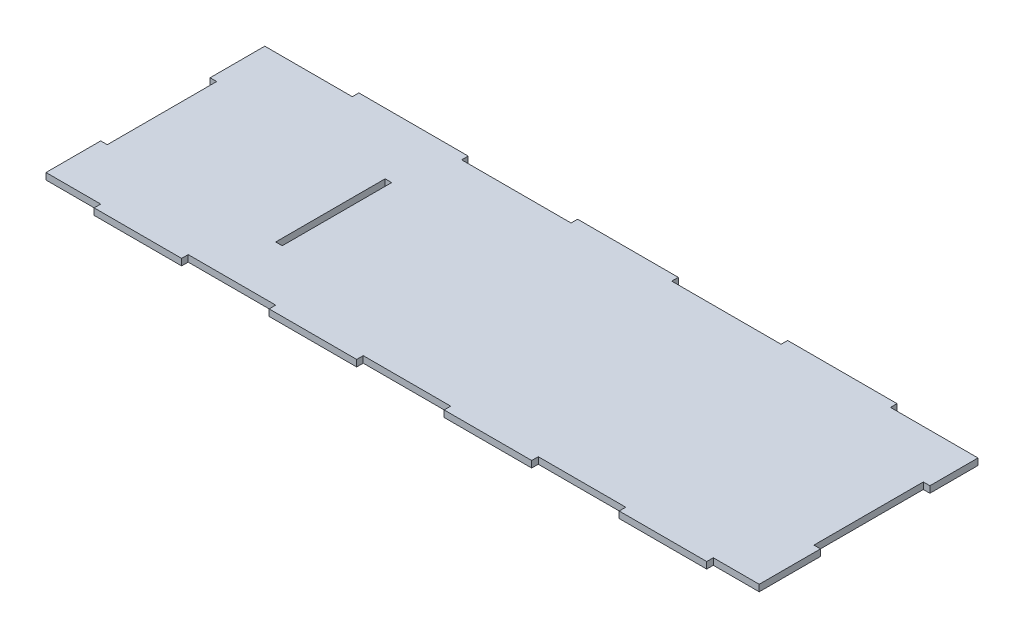
SolidWorks part; units mm, degrees
ref_plane "Front Plane" through (0, 0, 0) normal (0, 0, 1) x (1, 0, 0)
ref_plane "Top Plane" through (0, 0, 0) normal (0, 1, 0) x (1, 0, 0)
ref_plane "Right Plane" through (0, 0, 0) normal (1, 0, 0) x (0, 0, -1)
sketch "Sketch1" plane through (0, 0, 0) normal (0, 0, 1) x (1, 0, 0)
  line L1 (-163, 0) -> (163, 0)
  line L2 (-163, 0) -> (-163, -3)
  line L3 (-163, -3) -> (163, -3)
  line L4 (163, 0) -> (163, -3)
  dimension "D1" = 3
  dimension "D2" = 3
  dimension "D3" = 326
  dimension "D4" = 163
extrude "Boss-Extrude1" add sketch "Sketch1" along normal blind 100
sketch "Sketch2" plane through (0, 0, 0) normal (0, 0, -1) x (-1, 0, 0)
  line L0 (163, -3) -> (-163, -3) construction
  line L1 (-123, -3) -> (-73, -3)
  line L2 (-123, -3) -> (-123, 0)
  line L3 (-123, 0) -> (-73, 0)
  line L4 (-73, -3) -> (-73, 0)
  line L5 (-123, 0) -> (-123, -3) construction
  line L6 (-163, 0) -> (163, 0) construction
  line L7 (-73, -3) -> (-73, 0) construction
  line L8 (-23, 0) -> (-23, -3) construction
  line L9 (-23, -3) -> (23, -3)
  line L10 (-23, -3) -> (-23, 0)
  line L11 (-23, 0) -> (23, 0)
  line L12 (23, -3) -> (23, 0)
  line L13 (23, -3) -> (23, 0) construction
  line L14 (73, 0) -> (73, -3) construction
  line L15 (73, -3) -> (123, -3)
  line L16 (73, -3) -> (73, 0)
  line L17 (73, 0) -> (123, 0)
  line L18 (123, -3) -> (123, 0)
  line L19 (123, -3) -> (123, 0) construction
extrude "Boss-Extrude2" add sketch "Sketch2" along normal blind 3
sketch "Sketch3" plane through (0, -3, 0) normal (0, -1, 0) x (1, 0, 0)
  line L0 (-163, 100) -> (-163, 0) construction
  line L1 (-163, 25) -> (-160, 25)
  line L2 (-163, 25) -> (-163, 75)
  line L3 (-163, 75) -> (-160, 75)
  line L4 (-160, 25) -> (-160, 75)
  line L5 (-163, 100) -> (163, 100) construction
  dimension "D1" = 3
  dimension "D2" = 25
  dimension "D3" = 50
extrude "Cut-Extrude1" cut sketch "Sketch3" against normal blind 6
sketch "Sketch4" plane through (0, -3, 0) normal (0, -1, 0) x (1, 0, 0)
  line L0 (163, 100) -> (163, 0) construction
  line L1 (-83, 75) -> (-80, 75)
  line L2 (-83, 75) -> (-83, 25)
  line L3 (-83, 25) -> (-80, 25)
  line L4 (-80, 75) -> (-80, 25)
  line L5 (-73, 0) -> (-23, 0) construction
  dimension "D1" = 50
  dimension "D2" = 3
  dimension "D3" = 243
  dimension "D4" = 25
extrude "Cut-Extrude2" cut sketch "Sketch4" against normal blind 6
sketch "Sketch5" plane through (0, -3, 0) normal (0, -1, 0) x (1, 0, 0)
  line L0 (163, 100) -> (163, 0) construction
  line L1 (160, 72) -> (163, 72)
  line L2 (160, 72) -> (160, 22)
  line L3 (160, 22) -> (163, 22)
  line L4 (163, 72) -> (163, 22)
  line L5 (160, 22) -> (163, 22) construction
extrude "Cut-Extrude3" cut sketch "Sketch5" against normal blind 6
sketch "Sketch6" plane through (0, 0, 100) normal (0, 0, 1) x (1, 0, 0)
  line L0 (-163, -3) -> (163, -3) construction
  line L1 (-138, -3) -> (-98, -3)
  line L2 (-138, -3) -> (-138, 0)
  line L3 (-138, 0) -> (-98, 0)
  line L4 (-98, -3) -> (-98, 0)
  line L5 (-138, 0) -> (-138, -3) construction
  line L6 (163, 0) -> (-163, 0) construction
  line L7 (-98, -3) -> (-98, 0) construction
  line L8 (-18, -3) -> (-18, 0) construction
  line L9 (-18, 0) -> (-58, 0)
  line L10 (-18, 0) -> (-18, -3)
  line L11 (-18, -3) -> (-58, -3)
  line L12 (-58, 0) -> (-58, -3)
  line L13 (-58, 0) -> (-58, -3) construction
  line L14 (22, 0) -> (22, -3) construction
  line L15 (22, 0) -> (62, 0)
  line L16 (22, 0) -> (22, -3)
  line L17 (22, -3) -> (62, -3)
  line L18 (62, 0) -> (62, -3)
  line L19 (62, -3) -> (62, 0) construction
  line L20 (142, -3) -> (142, 0) construction
  line L21 (142, 0) -> (102, 0)
  line L22 (142, 0) -> (142, -3)
  line L23 (142, -3) -> (102, -3)
  line L24 (102, 0) -> (102, -3)
  line L25 (102, 0) -> (102, -3) construction
extrude "Boss-Extrude3" add sketch "Sketch6" along normal blind 3
